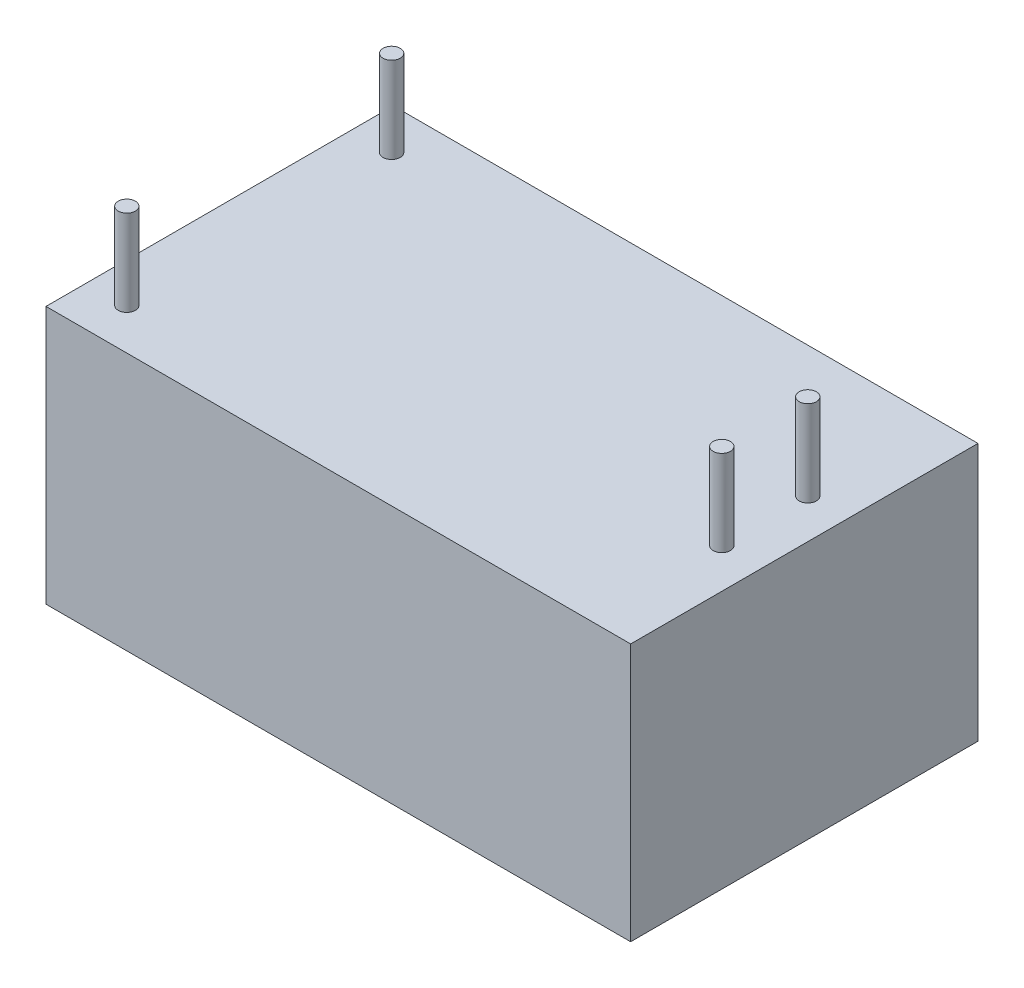
SolidWorks part; units mm, degrees
other "Marca1"
sketch "Croquis3" plane through (17, 20, -10.1) normal (0.0039, 0.9993, -0.0373) x (0.6692, -0.0303, -0.7425)
ref_plane "Alzado" through (0, 0, 0) normal (0, 0, 1) x (1, 0, 0)
ref_plane "Planta" through (0, 0, 0) normal (0, 1, 0) x (1, 0, 0)
ref_plane "Vista lateral" through (0, 0, 0) normal (1, 0, 0) x (0, 0, -1)
sketch "Croquis1" plane through (0, 0, 0) normal (0, 1, 0) x (1, 0, 0)
  line L1 (-17, -10.1) -> (17, -10.1)
  line L2 (-17, -10.1) -> (-17, 10.1)
  line L3 (-17, 10.1) -> (17, 10.1)
  line L4 (17, -10.1) -> (17, 10.1)
  line L5 (-17, -10.1) -> (17, 10.1) construction
  line L6 (-17, 10.1) -> (17, -10.1) construction
  point P0 (0, 0)
  dimension "D1" = 34
  dimension "D2" = 20.2
extrude "Saliente-Extruir1" add sketch "Croquis1" along normal blind 15
sketch "Croquis2" plane through (0, 15, 0) normal (0, 1, 0) x (1, 0, 0)
  line L0 (14.7, 2.5) -> (14.7, -2.5) construction
  line L1 (-14.7, 7.7) -> (-14.7, -7.7) construction
  line L2 (-14.7, 0) -> (14.7, 0) construction
  circle A0 centre (-14.7, 7.7) radius 0.5
  circle A1 centre (-14.7, -7.7) radius 0.5
  circle A2 centre (14.7, -2.5) radius 0.5
  circle A3 centre (14.7, 2.5) radius 0.5
  point P8 (14.7, 0)
  point P9 (-14.7, 0)
  point P13 (0, 0)
  dimension "D1" = 1
  dimension "D2" = 5
  dimension "D3" = 15.4
  dimension "D4" = 29.4
extrude "Saliente-Extruir2" add sketch "Croquis2" along normal blind 5
